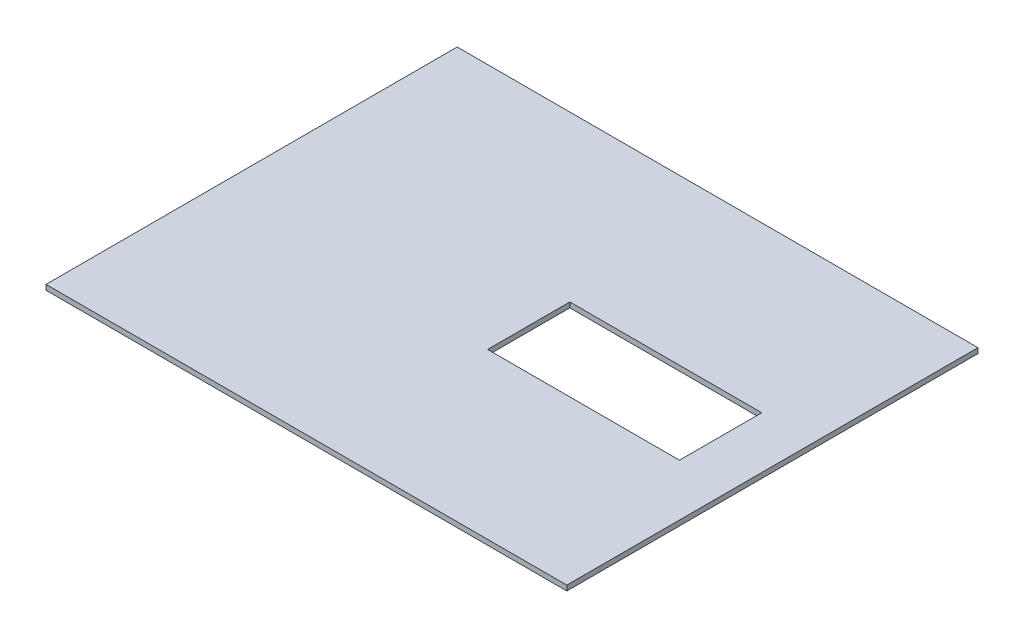
SolidWorks part; units mm, degrees
ref_plane "Front Plane" through (0, 0, 0) normal (0, 0, 1) x (1, 0, 0)
ref_plane "Top Plane" through (0, 0, 0) normal (0, 1, 0) x (1, 0, 0)
ref_plane "Right Plane" through (0, 0, 0) normal (1, 0, 0) x (0, 0, -1)
sketch "Sketch1" plane through (0, 0, 0) normal (0, 1, 0) x (1, 0, 0)
  line L1 (-241.3, 190.5) -> (241.3, 190.5)
  line L2 (-241.3, 190.5) -> (-241.3, -190.5)
  line L3 (-241.3, -190.5) -> (241.3, -190.5)
  line L4 (241.3, 190.5) -> (241.3, -190.5)
  line L5 (-241.3, 190.5) -> (241.3, -190.5) construction
  line L6 (-241.3, -190.5) -> (241.3, 190.5) construction
  point P0 (0, 0)
  dimension "D1" = 381
  dimension "D2" = 482.6
extrude "Boss-Extrude1" add sketch "Sketch1" along normal blind 4.7625
sketch "Sketch2" plane through (0, 4.7625, 0) normal (0, 1, 0) x (1, 0, 0)
  line L0 (0, 190.5) -> (0, -190.5) construction
  line L1 (241.3, 190.5) -> (-241.3, 190.5) construction
  line L2 (-241.3, -190.5) -> (241.3, -190.5) construction
sketch "Sketch3" plane through (0, 4.7625, 0) normal (0, 1, 0) x (1, 0, 0)
  line L0 (193.294, -190.5) -> (193.294, 190.5) construction
  line L1 (193.294, -38.1) -> (15.494, -38.1)
  line L2 (193.294, -38.1) -> (193.294, 38.1)
  line L3 (193.294, 38.1) -> (15.494, 38.1)
  line L4 (15.494, -38.1) -> (15.494, 38.1)
  line L5 (193.294, 165.1) -> (-193.294, 165.1) construction
  line L6 (-193.294, -165.1) -> (193.294, -165.1) construction
  dimension "D1" = 127
  dimension "D2" = 127
  dimension "D3" = 177.8
extrude "Cut-Extrude1" cut sketch "Sketch3" against normal up to surface (4.7625 mm away) up to face at (0, 0, 0)
